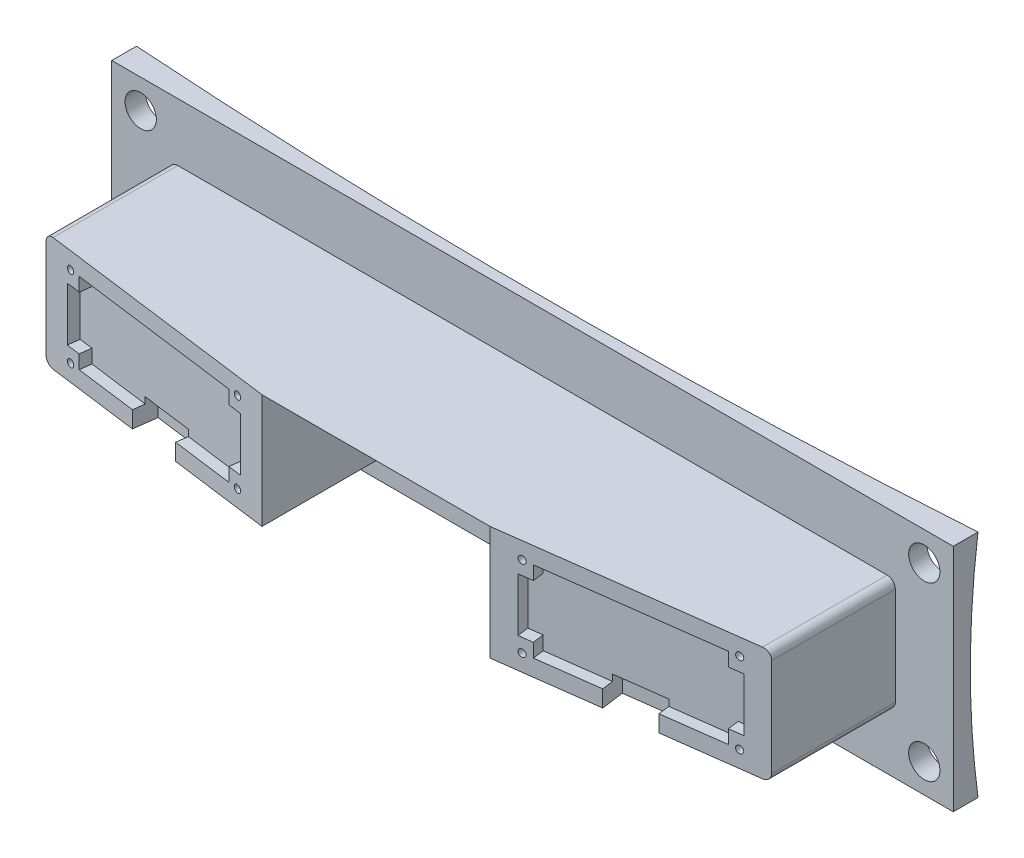
SolidWorks part; units mm, degrees
material "Nylon 101"
ref_plane "Front Plane" through (0, 0, 0) normal (0, 0, 1) x (1, 0, 0)
ref_plane "Top Plane" through (0, 0, 0) normal (0, 1, 0) x (1, 0, 0)
ref_plane "Right Plane" through (0, 0, 0) normal (1, 0, 0) x (0, 0, -1)
sketch "Sketch6" plane through (0, 0, 0) normal (0, 1, 0) x (1, 0, 0)
  line L6 (-79.5295, 0) -> (79.5295, 0)
  line L7 (-79.5295, 0) -> (-79.5295, -56.3211)
  line L8 (-79.5295, -56.3211) -> (-25, -63.5)
  line L9 (-25, -63.5) -> (25, -63.5)
  line L10 (25, -63.5) -> (79.5295, -56.3211)
  line L11 (79.5295, -56.3211) -> (79.5295, 0)
  line L12 (0, -63.5) -> (0, 0) construction
  point P4 (0, 0)
  point P10 (0, -63.5)
  dimension "D1" = 172.5
  dimension "D2" = 55
  dimension "D3" = 63.5
  dimension "D4" = 50
extrude "Boss-Extrude4" add sketch "Sketch6" along normal blind 25
sketch "Sketch7" plane through (0, 0, 0) normal (1, 0, 0) x (0, 0, -1)
  line L0 (-63.5, 25) -> (-38.5, 0)
  line L1 (-63.5, 0) -> (-56.3211, 0) construction
  line L2 (-63.5, 25) -> (-63.5, 0) construction
  line L3 (-63.5, 25) -> (-63.5, 0)
  line L4 (-63.5, 0) -> (-38.5, 0)
  dimension "D1" = 45
extrude "Cut-Extrude2" cut sketch "Sketch7" against normal mid plane 50
hole_wizard "Tap Drill for #4-40 Tap1" positions "Sketch9" profile "Sketch10" hole size "#4-40" standard "ANSI Inch"
sketch "Sketch9" plane through (0, -19.25, 19.25) normal (0, -0.7071, 0.7071) x (-1, 0, 0)
  line L0 (21.255, -53.7563) -> (21.255, -36.0463) construction
  line L2 (25, -27.2236) -> (25, -62.579) construction
  line L3 (21.255, -53.7563) -> (-21.255, -53.7563) construction
  line L5 (25, -62.579) -> (-25, -62.579) construction
  point P0 (-21.255, -53.7563)
  point P2 (21.255, -53.7563)
  point P4 (21.255, -36.0463)
  point P6 (-21.255, -36.0463)
  point P18 (21.255, -44.9013)
  point P21 (25, -44.9013)
  point P29 (0, -53.7563)
  point P32 (0, -62.579)
  dimension "D1" = 42.51
  dimension "D2" = 17.71
sketch "Sketch10" plane through (21.255, 18.7614, 57.2614) normal (1, 0, 0) x (0, -0.7071, -0.7071)
  line L0 (0, 0) -> (0, 8.3547)
  line L1 (0, 8.3547) -> (0.8, 7.874)
  line L2 (0.8, 7.874) -> (0.8, 0)
  line L5 (0.8, 0) -> (0, 0)
  line L10 (0, 8.3547) -> (-0.8, 7.874) construction
  line L11 (0, -6.35) -> (0, 107.95) construction
  dimension "Hole Dia." = 1.6
  dimension "Hole Depth" = 7.874
  dimension "Drill Angle" = 118
hole_wizard "Tap Drill for #4-40 Tap3" positions "Sketch14" profile "Sketch15" hole size "#4-40" standard "ANSI Inch"
sketch "Sketch14" plane through (-8.6434, 0, 65.6534) normal (-0.1305, 0, 0.9914) x (0.9914, 0, 0.1305)
  line L2 (-22.7427, 21.355) -> (-65.2527, 21.355) construction
  line L3 (-65.2527, 21.355) -> (-65.2527, 3.645) construction
  line L5 (-71.4977, 25) -> (-16.4977, 25) construction
  line L6 (-71.4977, 25) -> (-71.4977, 0) construction
  point P0 (-65.2527, 21.355)
  point P12 (-22.7427, 21.355)
  point P13 (-22.7427, 3.645)
  point P14 (-65.2527, 3.645)
  point P26 (-43.9977, 21.355)
  point P29 (-43.9977, 25)
  point P30 (-65.2527, 12.5)
  point P33 (-71.4977, 12.5)
  dimension "D3" = 42.51
  dimension "D4" = 17.71
  dimension "D1" = 2
  dimension "D2" = 2
sketch "Sketch15" plane through (-73.3379, 21.355, 57.1362) normal (0, 1, 0) x (0.9914, 0, 0.1305)
  line L0 (0, 0) -> (0, 8.3547)
  line L1 (0, 8.3547) -> (0.8, 7.874)
  line L2 (0.8, 7.874) -> (0.8, 0)
  line L5 (0.8, 0) -> (0, 0)
  line L10 (0, 8.3547) -> (-0.8, 7.874) construction
  line L11 (0, -6.35) -> (0, 107.95) construction
  dimension "Hole Dia." = 1.6
  dimension "Hole Depth" = 7.874
  dimension "Drill Angle" = 118
hole_wizard "Tap Drill for #4-40 Tap4" positions "Sketch18" profile "Sketch19" hole size "#4-40" standard "ANSI Inch"
sketch "Sketch18" plane through (8.6434, 0, 65.6534) normal (0.1305, 0, 0.9914) x (0.9914, 0, -0.1305)
  line L2 (22.7427, 3.645) -> (22.7427, 21.355) construction
  line L3 (22.7427, 21.355) -> (65.2527, 21.355) construction
  line L6 (16.4977, 25) -> (71.4977, 25) construction
  line L7 (16.4977, 25) -> (16.4977, 0) construction
  point P0 (22.7427, 21.355)
  point P9 (65.2527, 21.355)
  point P10 (65.2527, 3.645)
  point P11 (22.7427, 3.645)
  point P22 (43.9977, 21.355)
  point P25 (43.9977, 25)
  point P26 (22.7427, 12.5)
  point P29 (16.4977, 12.5)
  dimension "D3" = 42.51
  dimension "D4" = 17.71
  dimension "D1" = 2
  dimension "D2" = 2
sketch "Sketch19" plane through (31.1916, 21.355, 62.6849) normal (0, 1, 0) x (0.9914, 0, -0.1305)
  line L0 (0, 0) -> (0, 8.3547)
  line L1 (0, 8.3547) -> (0.8, 7.874)
  line L2 (0.8, 7.874) -> (0.8, 0)
  line L5 (0.8, 0) -> (0, 0)
  line L10 (0, 8.3547) -> (-0.8, 7.874) construction
  line L11 (0, -6.35) -> (0, 107.95) construction
  dimension "Hole Dia." = 1.6
  dimension "Hole Depth" = 7.874
  dimension "Drill Angle" = 118
fillet "Fillet1" radius 1.778 4 edges at (79.5295, 25, 28.1605) (79.5295, 0, 28.1605) (-79.5295, 0, 28.1605) (-79.5295, 25, 28.1605)
sketch "Sketch20" plane through (-8.6434, 0, 65.6534) normal (-0.1305, 0, 0.9914) x (0.9914, 0, 0.1305)
  line L0 (-63.0527, 21.355) -> (-63.0527, 18.355)
  line L1 (-63.0527, 18.355) -> (-66.0527, 18.355)
  line L2 (-66.0527, 18.355) -> (-66.0527, 6.645)
  line L3 (-66.0527, 6.645) -> (-63.0527, 6.645)
  line L4 (-63.0527, 6.645) -> (-63.0527, 3.645)
  line L5 (-63.0527, 3.645) -> (-24.9427, 3.645)
  line L6 (-24.9427, 3.645) -> (-24.9427, 6.645)
  line L7 (-24.9427, 6.645) -> (-21.9427, 6.645)
  line L8 (-21.9427, 6.645) -> (-21.9427, 18.355)
  line L9 (-21.9427, 18.355) -> (-24.9427, 18.355)
  line L10 (-24.9427, 18.355) -> (-24.9427, 21.355)
  line L11 (-24.9427, 21.355) -> (-63.0527, 21.355)
  circle A2 centre (-65.2527, 21.355) radius 0.8 construction
  circle A3 centre (-65.2527, 21.355) radius 0.8 construction
  circle A4 centre (-22.7427, 21.355) radius 0.8 construction
  point P11 (-66.0527, 21.355)
  point P14 (-21.9427, 21.355)
  dimension "D1" = 3
  dimension "D2" = 3
sketch "Sketch21" plane through (8.6434, 0, 65.6534) normal (0.1305, 0, 0.9914) x (0.9914, 0, -0.1305)
  line L0 (24.9427, 21.355) -> (24.9427, 18.355)
  line L1 (24.9427, 18.355) -> (21.9427, 18.355)
  line L2 (21.9427, 18.355) -> (21.9427, 6.645)
  line L3 (21.9427, 6.645) -> (24.9427, 6.645)
  line L4 (24.9427, 6.645) -> (24.9427, 3.645)
  line L5 (24.9427, 3.645) -> (63.0527, 3.645)
  line L6 (63.0527, 3.645) -> (63.0527, 6.645)
  line L7 (63.0527, 6.645) -> (66.0527, 6.645)
  line L8 (66.0527, 6.645) -> (66.0527, 18.355)
  line L9 (66.0527, 18.355) -> (63.0527, 18.355)
  line L10 (63.0527, 18.355) -> (63.0527, 21.355)
  line L11 (63.0527, 21.355) -> (24.9427, 21.355)
  circle A0 centre (22.7427, 21.355) radius 0.8 construction
  circle A1 centre (22.7427, 21.355) radius 0.8 construction
  circle A2 centre (65.2527, 21.355) radius 0.8 construction
  circle A3 centre (65.2527, 21.355) radius 0.8 construction
  point P11 (21.9427, 21.355)
  point P14 (66.0527, 21.355)
  dimension "D1" = 3
  dimension "D2" = 3
sketch "Sketch22" plane through (0, -19.25, 19.25) normal (0, -0.7071, 0.7071) x (1, 0, 0)
  line L0 (-19.055, 53.7563) -> (-19.055, 50.7563)
  line L1 (-19.055, 50.7563) -> (-22.055, 50.7563)
  line L2 (-22.055, 50.7563) -> (-22.055, 39.0463)
  line L3 (-22.055, 39.0463) -> (-19.055, 39.0463)
  line L4 (-19.055, 39.0463) -> (-19.055, 36.0463)
  line L5 (-19.055, 36.0463) -> (19.055, 36.0463)
  line L6 (19.055, 36.0463) -> (19.055, 39.0463)
  line L7 (19.055, 39.0463) -> (22.055, 39.0463)
  line L8 (22.055, 39.0463) -> (22.055, 50.7563)
  line L9 (22.055, 50.7563) -> (19.055, 50.7563)
  line L10 (19.055, 50.7563) -> (19.055, 53.7563)
  line L11 (19.055, 53.7563) -> (-19.055, 53.7563)
  circle A0 centre (-21.255, 53.7563) radius 0.8 construction
  circle A1 centre (-21.255, 53.7563) radius 0.8 construction
  circle A2 centre (21.255, 53.7563) radius 0.8 construction
  circle A3 centre (21.255, 53.7563) radius 0.8 construction
  point P18 (22.055, 53.7563)
  point P25 (-22.055, 53.7563)
  dimension "D1" = 3
  dimension "D2" = 3
extrude "Cut-Extrude3" cut sketch "Sketch22" against normal blind 2.5
extrude "Cut-Extrude4" cut sketch "Sketch21" against normal blind 2.5 contours L5 L6 L7 L8 L9 L10 L11 L0 L1 L2 L3 L4
extrude "Cut-Extrude5" cut sketch "Sketch20" against normal blind 2.5 contours L5 L6 L7 L8 L9 L10 L11 L0 L1 L2 L3 L4
sketch "Sketch23" plane through (8.6434, 0, 65.6534) normal (0.1305, 0, 0.9914) x (0.9914, 0, -0.1305)
  line L1 (38.4977, 5.045) -> (49.4977, 5.045)
  line L2 (38.4977, 5.045) -> (38.4977, 0)
  line L3 (38.4977, 0) -> (49.4977, 0)
  line L4 (49.4977, 5.045) -> (49.4977, 0)
  line L5 (24.9427, 3.645) -> (63.0527, 3.645) construction
  line L6 (24.9427, 3.645) -> (63.0527, 3.645) construction
  line L7 (16.4977, 0) -> (69.7044, 0) construction
  point P0 (43.9977, 5.045)
  point P12 (43.9977, 3.645)
  dimension "D1" = 11
  dimension "D2" = 1.4
extrude "Cut-Extrude6" cut sketch "Sketch23" against normal blind 5
sketch "Sketch24" plane through (-8.6434, 0, 65.6534) normal (-0.1305, 0, 0.9914) x (0.9914, 0, 0.1305)
  line L0 (-49.4977, 5.045) -> (-38.4977, 5.045)
  line L1 (-49.4977, 5.045) -> (-49.4977, 0)
  line L2 (-49.4977, 0) -> (-38.4977, 0)
  line L3 (-38.4977, 5.045) -> (-38.4977, 0)
  line L4 (-63.0527, 3.645) -> (-24.9427, 3.645) construction
  line L5 (-69.7044, 0) -> (-16.4977, 0) construction
  point P0 (-43.9977, 5.045)
  point P7 (-43.9977, 3.645)
  dimension "D1" = 11
  dimension "D2" = 1.4
extrude "Cut-Extrude7" cut sketch "Sketch24" against normal blind 5
sketch "Sketch25" plane through (0, -19.25, 19.25) normal (0, -0.7071, 0.7071) x (1, 0, 0)
  line L0 (-5.5, 37.4463) -> (5.5, 37.4463)
  line L1 (-5.5, 37.4463) -> (-5.5, 21.3712)
  line L2 (-5.5, 21.3712) -> (5.5, 21.3712)
  line L3 (5.5, 37.4463) -> (5.5, 21.3712)
  line L4 (-19.055, 36.0463) -> (19.055, 36.0463) construction
  point P0 (0, 37.4463)
  point P7 (0, 36.0463)
  dimension "D1" = 11
  dimension "D2" = 1.4
extrude "Cut-Extrude8" cut sketch "Sketch25" against normal blind 10 contours L3 L2 L1 L0
sketch "Sketch26" plane through (0, 0, 0) normal (0, 0, -1) x (-1, 0, 0)
  line L0 (-77.7515, 25) -> (77.7515, 25) construction
  line L1 (-92.2295, -12.7) -> (92.2295, -12.7)
  line L2 (-92.2295, -12.7) -> (-92.2295, 37.7)
  line L3 (-92.2295, 37.7) -> (92.2295, 37.7)
  line L4 (92.2295, -12.7) -> (92.2295, 37.7)
  line L5 (-92.2295, -12.7) -> (92.2295, 37.7) construction
  line L6 (-92.2295, 37.7) -> (92.2295, -12.7) construction
  line L7 (-79.5295, 23.222) -> (-79.5295, 1.778) construction
  point P0 (0, 12.5)
  point P9 (0, 37.7)
  point P11 (-92.2295, 12.5)
  point P12 (-79.5295, 12.5)
  dimension "D1" = 12.7
  dimension "D2" = 12.7
extrude "Boss-Extrude6" add sketch "Sketch26" against normal blind 29.21
sketch "Sketch11" plane through (0, 0, 0) normal (1, 0, 0) x (0, 0, -1)
  line L0 (-28.575, 12.5) -> (1344.295, 12.5) construction
  line L1 (0, 25) -> (0, 0) construction
  line L2 (1344.295, -496.77) -> (1344.295, 521.77)
  ellipse E0 centre (1344.295, 12.5) end of major axis (-28.575, 12.5) minor radius 509.27 (1344.295, 521.77) -> (1344.295, -496.77) ccw
  point P7 (1344.295, 12.5)
  point P15 (0, 12.5)
  dimension "D1" = 1372.87
  dimension "D2" = 1018.54
  dimension "D3" = 28.575
revolve "Cut-Revolve4" cut sketch "Sketch11" angle 360 about L2
sketch "Sketch27" plane through (0, 0, 29.21) normal (0, 0, 1) x (1, 0, 0)
  line L0 (92.2295, 37.7) -> (92.2295, -12.7) construction
  line L1 (92.2295, -12.7) -> (-92.2295, -12.7) construction
  line L2 (-92.2295, 37.7) -> (92.2295, 37.7) construction
  line L3 (-92.2295, -12.7) -> (-92.2295, 37.7) construction
  circle A0 centre (85.8795, -6.35) radius 3.429
  circle A1 centre (-85.8795, -6.35) radius 3.429
  circle A2 centre (-85.8795, 31.35) radius 3.429
  circle A3 centre (85.8795, 31.35) radius 3.429
  dimension "D1" = 6.858
  dimension "D2" = 6.35
  dimension "D6" = 6.35
  dimension "D7" = 6.35
  dimension "D3" = 6.35
  dimension "D4" = 2
  dimension "D5" = 2
extrude "Cut-Extrude9" cut sketch "Sketch27" against normal through all
